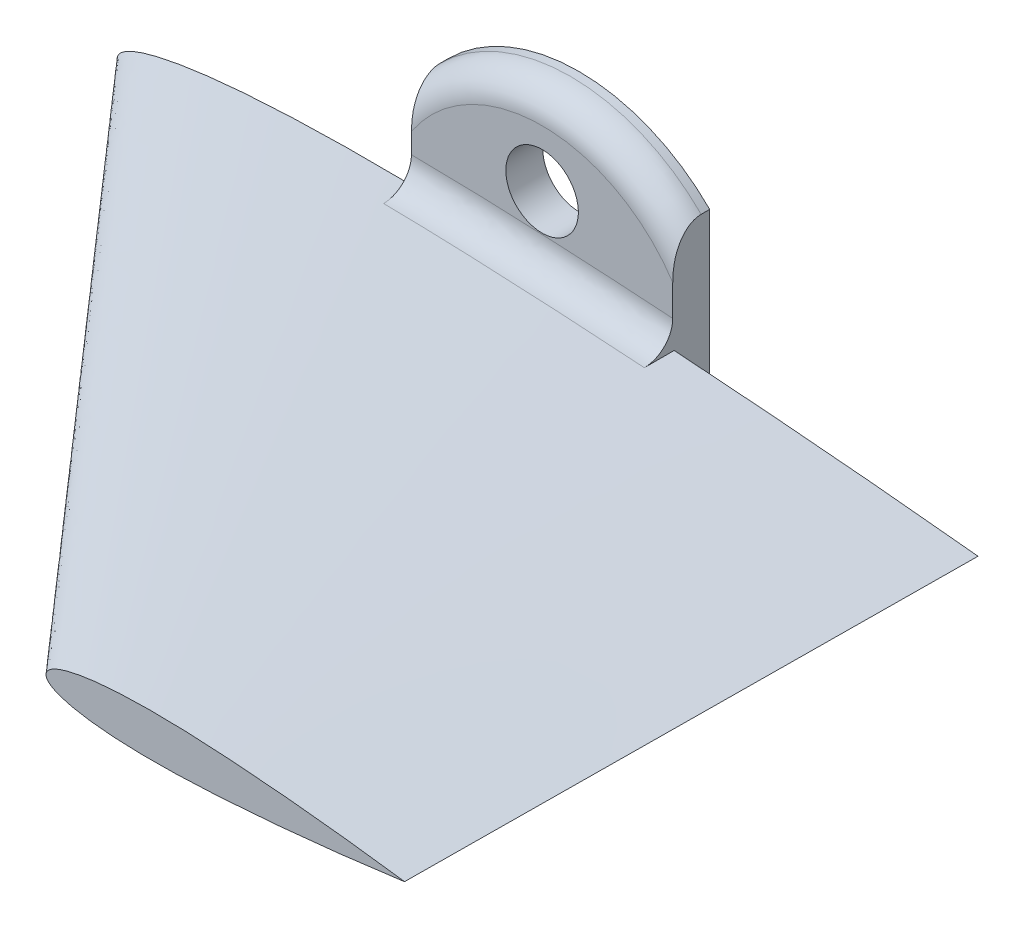
SolidWorks part; units mm, degrees
ref_plane "Front Plane" through (0, 0, 0) normal (0, 0, 1) x (1, 0, 0)
ref_plane "Top Plane" through (0, 0, 0) normal (0, 1, 0) x (1, 0, 0)
ref_plane "Right Plane" through (0, 0, 0) normal (1, 0, 0) x (0, 0, -1)
curve "BigAirfoilSketch"
  spline degree 3 poles (60, -0.0567, 0) (59.9883, -0.0579, 0) (59.9416, -0.0628, 0) (59.8367, -0.0739, 0) (59.6621, -0.0922, 0) (59.4182, -0.1176, 0) (59.1056, -0.15, 0) (58.725, -0.1892, 0) (58.2773, -0.2349, 0) (57.7636, -0.2868, 0) (57.1851, -0.3447, 0) (56.543, -0.4081, 0) (55.839, -0.4768, 0) (55.0746, -0.5503, 0) (54.2517, -0.6281, 0) (53.3721, -0.71, 0) (52.4379, -0.7954, 0) (51.4513, -0.884, 0) (50.4147, -0.9753, 0) (49.3303, -1.0688, 0) (48.2008, -1.1641, 0) (47.0288, -1.2607, 0) (45.817, -1.3582, 0) (44.5683, -1.4561, 0) (43.2855, -1.554, 0) (41.9717, -1.6513, 0) (40.63, -1.7476, 0) (39.2634, -1.8424, 0) (37.8752, -1.935, 0) (36.4686, -2.0251, 0) (35.0469, -2.112, 0) (33.6134, -2.1952, 0) (32.1715, -2.2742, 0) (30.7245, -2.3482, 0) (29.2758, -2.4169, 0) (27.8288, -2.4795, 0) (26.3868, -2.5354, 0) (24.9533, -2.5842, 0) (23.5316, -2.6253, 0) (22.125, -2.6582, 0) (20.7368, -2.6822, 0) (19.3702, -2.6971, 0) (18.0284, -2.7024, 0) (16.7146, -2.6978, 0) (15.4318, -2.6829, 0) (14.183, -2.6576, 0) (12.9711, -2.6217, 0) (11.799, -2.5751, 0) (10.6694, -2.5179, 0) (9.585, -2.4501, 0) (8.5482, -2.3718, 0) (7.5614, -2.2834, 0) (6.6271, -2.1852, 0) (5.7473, -2.0773, 0) (4.9241, -1.9604, 0) (4.1594, -1.8348, 0) (3.455, -1.7011, 0) (2.8124, -1.5597, 0) (2.2332, -1.4113, 0) (1.7185, -1.2562, 0) (1.2695, -1.0952, 0) (0.8868, -0.9286, 0) (0.5711, -0.7567, 0) (0.3223, -0.5794, 0) (0.1403, -0.3957, 0) (0.0264, -0.2025, 0) (-0.0125, 0, 0) (0.0264, 0.2025, 0) (0.1403, 0.3957, 0) (0.3223, 0.5794, 0) (0.5711, 0.7567, 0) (0.8868, 0.9286, 0) (1.2695, 1.0952, 0) (1.7185, 1.2562, 0) (2.2332, 1.4113, 0) (2.8124, 1.5597, 0) (3.455, 1.7011, 0) (4.1594, 1.8348, 0) (4.9241, 1.9604, 0) (5.7473, 2.0773, 0) (6.6271, 2.1852, 0) (7.5614, 2.2834, 0) (8.5482, 2.3718, 0) (9.585, 2.4501, 0) (10.6694, 2.5179, 0) (11.799, 2.5751, 0) (12.9711, 2.6217, 0) (14.183, 2.6576, 0) (15.4318, 2.6829, 0) (16.7146, 2.6978, 0) (18.0284, 2.7024, 0) (19.3702, 2.6971, 0) (20.7368, 2.6822, 0) (22.125, 2.6582, 0) (23.5316, 2.6253, 0) (24.9533, 2.5842, 0) (26.3868, 2.5354, 0) (27.8288, 2.4795, 0) (29.2758, 2.4169, 0) (30.7245, 2.3482, 0) (32.1715, 2.2742, 0) (33.6134, 2.1952, 0) (35.0469, 2.112, 0) (36.4686, 2.0251, 0) (37.8752, 1.935, 0) (39.2634, 1.8424, 0) (40.63, 1.7476, 0) (41.9717, 1.6513, 0) (43.2855, 1.554, 0) (44.5683, 1.4561, 0) (45.817, 1.3582, 0) (47.0288, 1.2607, 0) (48.2008, 1.1641, 0) (49.3303, 1.0688, 0) (50.4147, 0.9753, 0) (51.4513, 0.884, 0) (52.4379, 0.7954, 0) (53.3721, 0.71, 0) (54.2517, 0.6281, 0) (55.0746, 0.5503, 0) (55.839, 0.4768, 0) (56.543, 0.4081, 0) (57.1851, 0.3447, 0) (57.7636, 0.2868, 0) (58.2773, 0.2349, 0) (58.725, 0.1892, 0) (59.1056, 0.15, 0) (59.4182, 0.1176, 0) (59.6621, 0.0922, 0) (59.8367, 0.0739, 0) (59.9416, 0.0628, 0) (59.9883, 0.0579, 0) (60, 0.0567, 0) knots 0 0 0 0 0.00029 0.001159 0.002606 0.004627 0.007216 0.010369 0.014077 0.018331 0.023122 0.028438 0.034267 0.040595 0.047406 0.054685 0.062414 0.070576 0.079152 0.08812 0.09746 0.10715 0.117167 0.127488 0.138088 0.148943 0.160027 0.171315 0.182779 0.194393 0.206129 0.217961 0.22986 0.241798 0.253749 0.265683 0.277573 0.289392 0.301111 0.312704 0.324145 0.335405 0.346461 0.357287 0.367857 0.378149 0.388138 0.397803 0.407122 0.416074 0.424641 0.432803 0.440543 0.447846 0.454696 0.461079 0.466985 0.472404 0.477327 0.481752 0.485676 0.489104 0.49205 0.494541 0.496625 0.498395 0.5 0.501605 0.503375 0.505459 0.50795 0.510896 0.514324 0.518248 0.522673 0.527596 0.533015 0.538921 0.545304 0.552154 0.559457 0.567197 0.575359 0.583926 0.592878 0.602197 0.611862 0.621851 0.632143 0.642713 0.653539 0.664595 0.675855 0.687296 0.698889 0.710608 0.722427 0.734317 0.746251 0.758202 0.77014 0.782039 0.793871 0.805607 0.817221 0.828685 0.839973 0.851057 0.861912 0.872512 0.882833 0.89285 0.90254 0.91188 0.920848 0.929424 0.937586 0.945315 0.952594 0.959405 0.965733 0.971562 0.976878 0.981669 0.985923 0.989631 0.992784 0.995373 0.997394 0.998841 0.99971 1 1 1 1
sketch "Sketch11" plane through (0, 0, 0) normal (0, 0, 1) x (1, 0, 0)
  line L0 (59.9926, -0.0575) -> (60.5673, -0.003)
  line L1 (60, 0.0567) -> (60.5673, -0.003)
  spline S0 degree 3 poles (318.1925, -1983.0716) (92.5981, 4.8069) (76.3215, 1.6568) (59.8367, -0.0739) (59.4309, -0.1164) (58.9107, -0.1702) (58.0844, -0.2546) (57.3565, -0.3278) (56.543, -0.4081) (55.839, -0.4768) (55.0746, -0.5503) (54.2517, -0.6281) (53.3721, -0.71) (51.7306, -0.8601) (50.0055, -1.0118) (48.2008, -1.1641) (46.6123, -1.295) (44.9726, -1.4253) (42.8381, -1.5881) (40.6055, -1.751) (38.3313, -1.9058) (35.9906, -2.0557) (34.0879, -2.1693) (32.1715, -2.2742) (30.7245, -2.3482) (29.2758, -2.4169) (27.8288, -2.4795) (26.3868, -2.5354) (24.9533, -2.5842) (23.5316, -2.6253) (22.125, -2.6582) (20.7368, -2.6822) (19.3702, -2.6971) (18.0284, -2.7024) (16.7146, -2.6978) (15.4318, -2.6829) (14.183, -2.6576) (12.9711, -2.6217) (11.799, -2.5751) (10.6694, -2.5179) (9.585, -2.4501) (8.5482, -2.3718) (7.5614, -2.2834) (6.6271, -2.1852) (5.7473, -2.0773) (4.9241, -1.9604) (4.1594, -1.8348) (3.455, -1.7011) (2.8124, -1.5597) (2.2332, -1.4113) (1.7185, -1.2562) (1.2695, -1.0952) (0.8868, -0.9286) (0.5711, -0.7567) (0.3223, -0.5794) (0.1403, -0.3957) (0.0264, -0.2025) (-0.0125, 0) (0.0264, 0.2025) (0.1403, 0.3957) (0.3223, 0.5794) (0.5711, 0.7567) (0.8868, 0.9286) (1.2695, 1.0952) (1.7185, 1.2562) (2.2332, 1.4113) (2.8124, 1.5597) (3.455, 1.7011) (4.1594, 1.8348) (4.9241, 1.9604) (5.7473, 2.0773) (6.6271, 2.1852) (7.5614, 2.2834) (8.5482, 2.3718) (9.585, 2.4501) (10.6694, 2.5179) (11.799, 2.5751) (12.9711, 2.6217) (14.183, 2.6576) (15.4318, 2.6829) (16.7146, 2.6978) (18.0284, 2.7024) (19.3702, 2.6971) (20.7368, 2.6822) (22.125, 2.6582) (23.5316, 2.6253) (24.9533, 2.5842) (26.3868, 2.5354) (27.8288, 2.4795) (29.2758, 2.4169) (30.7245, 2.3482) (32.1715, 2.2742) (34.0879, 2.1693) (35.9906, 2.0557) (38.3313, 1.9058) (40.6055, 1.751) (43.2548, 1.5578) (45.3892, 1.3926) (47.0288, 1.2607) (48.2008, 1.1641) (49.6762, 1.0396) (51.0897, 0.9165) (52.4379, 0.7954) (53.3721, 0.71) (54.2517, 0.6281) (55.0746, 0.5503) (55.839, 0.4768) (56.543, 0.4081) (57.5059, 0.313) (58.465, 0.2162) (59.2912, 0.1308) (59.6621, 0.0922) (59.8367, 0.0739) (76.3212, -1.6567) (92.5976, -4.8068) (318.1829, 1982.9864) knots -0.406809 -0.406809 -0.406809 -0.406809 0.00029 0.001159 0.002606 0.010369 0.014077 0.023122 0.028438 0.034267 0.040595 0.047406 0.054685 0.062414 0.08812 0.09746 0.10715 0.127488 0.138088 0.160027 0.182779 0.194393 0.217961 0.22986 0.241798 0.253749 0.265683 0.277573 0.289392 0.301111 0.312704 0.324145 0.335405 0.346461 0.357287 0.367857 0.378149 0.388138 0.397803 0.407122 0.416074 0.424641 0.432803 0.440543 0.447846 0.454696 0.461079 0.466985 0.472404 0.477327 0.481752 0.485676 0.489104 0.49205 0.494541 0.496625 0.498395 0.5 0.501605 0.503375 0.505459 0.50795 0.510896 0.514324 0.518248 0.522673 0.527596 0.533015 0.538921 0.545304 0.552154 0.559457 0.567197 0.575359 0.583926 0.592878 0.602197 0.611862 0.621851 0.632143 0.642713 0.653539 0.664595 0.675855 0.687296 0.698889 0.710608 0.722427 0.734317 0.746251 0.758202 0.77014 0.782039 0.805607 0.817221 0.839973 0.861912 0.882833 0.89285 0.90254 0.91188 0.929424 0.937586 0.945315 0.952594 0.959405 0.965733 0.971562 0.976878 0.989631 0.995373 0.997394 0.998841 0.99971 1.406803 1.406803 1.406803 1.406803 only from (60, -0.0567) to (60, 0.0567) construction
  spline S1 degree 3 poles (59.9926, -0.0575) (59.9834, -0.0584) (59.9392, -0.0631) (59.8367, -0.0739) (59.4309, -0.1164) (58.9107, -0.1702) (58.0844, -0.2546) (57.3565, -0.3278) (56.543, -0.4081) (55.839, -0.4768) (55.0746, -0.5503) (54.2517, -0.6281) (53.3721, -0.71) (51.7306, -0.8601) (50.0055, -1.0118) (48.2008, -1.1641) (46.6123, -1.295) (44.9726, -1.4253) (42.8381, -1.5881) (40.6055, -1.751) (38.3313, -1.9058) (35.9906, -2.0557) (34.0879, -2.1693) (32.1715, -2.2742) (30.7245, -2.3482) (29.2758, -2.4169) (27.8288, -2.4795) (26.3868, -2.5354) (24.9533, -2.5842) (23.5316, -2.6253) (22.125, -2.6582) (20.7368, -2.6822) (19.3702, -2.6971) (18.0284, -2.7024) (16.7146, -2.6978) (15.4318, -2.6829) (14.183, -2.6576) (12.9711, -2.6217) (11.799, -2.5751) (10.6694, -2.5179) (9.585, -2.4501) (8.5482, -2.3718) (7.5614, -2.2834) (6.6271, -2.1852) (5.7473, -2.0773) (4.9241, -1.9604) (4.1594, -1.8348) (3.455, -1.7011) (2.8124, -1.5597) (2.2332, -1.4113) (1.7185, -1.2562) (1.2695, -1.0952) (0.8868, -0.9286) (0.5711, -0.7567) (0.3223, -0.5794) (0.1403, -0.3957) (0.0264, -0.2025) (-0.0125, 0) (0.0264, 0.2025) (0.1403, 0.3957) (0.3223, 0.5794) (0.5711, 0.7567) (0.8868, 0.9286) (1.2695, 1.0952) (1.7185, 1.2562) (2.2332, 1.4113) (2.8124, 1.5597) (3.455, 1.7011) (4.1594, 1.8348) (4.9241, 1.9604) (5.7473, 2.0773) (6.6271, 2.1852) (7.5614, 2.2834) (8.5482, 2.3718) (9.585, 2.4501) (10.6694, 2.5179) (11.799, 2.5751) (12.9711, 2.6217) (14.183, 2.6576) (15.4318, 2.6829) (16.7146, 2.6978) (18.0284, 2.7024) (19.3702, 2.6971) (20.7368, 2.6822) (22.125, 2.6582) (23.5316, 2.6253) (24.9533, 2.5842) (26.3868, 2.5354) (27.8288, 2.4795) (29.2758, 2.4169) (30.7245, 2.3482) (32.1715, 2.2742) (34.0879, 2.1693) (35.9906, 2.0557) (38.3313, 1.9058) (40.6055, 1.751) (43.2548, 1.5578) (45.3892, 1.3926) (47.0288, 1.2607) (48.2008, 1.1641) (49.6762, 1.0396) (51.0897, 0.9165) (52.4379, 0.7954) (53.3721, 0.71) (54.2517, 0.6281) (55.0746, 0.5503) (55.839, 0.4768) (56.543, 0.4081) (57.5059, 0.313) (58.465, 0.2162) (59.2912, 0.1308) (59.6621, 0.0922) (59.8367, 0.0739) (59.9416, 0.0628) (59.9883, 0.0579) (60, 0.0567) knots 0.000061 0.000061 0.000061 0.000061 0.00029 0.001159 0.002606 0.010369 0.014077 0.023122 0.028438 0.034267 0.040595 0.047406 0.054685 0.062414 0.08812 0.09746 0.10715 0.127488 0.138088 0.160027 0.182779 0.194393 0.217961 0.22986 0.241798 0.253749 0.265683 0.277573 0.289392 0.301111 0.312704 0.324145 0.335405 0.346461 0.357287 0.367857 0.378149 0.388138 0.397803 0.407122 0.416074 0.424641 0.432803 0.440543 0.447846 0.454696 0.461079 0.466985 0.472404 0.477327 0.481752 0.485676 0.489104 0.49205 0.494541 0.496625 0.498395 0.5 0.501605 0.503375 0.505459 0.50795 0.510896 0.514324 0.518248 0.522673 0.527596 0.533015 0.538921 0.545304 0.552154 0.559457 0.567197 0.575359 0.583926 0.592878 0.602197 0.611862 0.621851 0.632143 0.642713 0.653539 0.664595 0.675855 0.687296 0.698889 0.710608 0.722427 0.734317 0.746251 0.758202 0.77014 0.782039 0.805607 0.817221 0.839973 0.861912 0.882833 0.89285 0.90254 0.91188 0.929424 0.937586 0.945315 0.952594 0.959405 0.965733 0.971562 0.976878 0.989631 0.995373 0.997394 0.998841 0.99971 1 1 1 1
curve "SmallAirfoilSketch"
  spline degree 3 poles (60, -0.0315, 40) (59.9951, -0.0322, 40) (59.9757, -0.0349, 40) (59.932, -0.041, 40) (59.8592, -0.0512, 40) (59.7576, -0.0653, 40) (59.6273, -0.0833, 40) (59.4688, -0.1051, 40) (59.2822, -0.1305, 40) (59.0682, -0.1594, 40) (58.8271, -0.1915, 40) (58.5596, -0.2267, 40) (58.2663, -0.2649, 40) (57.9478, -0.3057, 40) (57.6049, -0.349, 40) (57.2384, -0.3944, 40) (56.8492, -0.4419, 40) (56.4381, -0.4911, 40) (56.0061, -0.5418, 40) (55.5543, -0.5938, 40) (55.0837, -0.6467, 40) (54.5954, -0.7004, 40) (54.0904, -0.7546, 40) (53.5701, -0.809, 40) (53.0357, -0.8633, 40) (52.4883, -0.9174, 40) (51.9292, -0.9709, 40) (51.3598, -1.0235, 40) (50.7814, -1.075, 40) (50.1953, -1.1251, 40) (49.6029, -1.1733, 40) (49.0056, -1.2196, 40) (48.4048, -1.2634, 40) (47.8019, -1.3046, 40) (47.1983, -1.3427, 40) (46.5954, -1.3775, 40) (45.9946, -1.4086, 40) (45.3973, -1.4357, 40) (44.8049, -1.4585, 40) (44.2188, -1.4768, 40) (43.6403, -1.4901, 40) (43.0709, -1.4984, 40) (42.5118, -1.5014, 40) (41.9644, -1.4988, 40) (41.4299, -1.4905, 40) (40.9095, -1.4764, 40) (40.4046, -1.4565, 40) (39.9162, -1.4306, 40) (39.4455, -1.3988, 40) (38.9936, -1.3611, 40) (38.5615, -1.3177, 40) (38.1504, -1.2685, 40) (37.761, -1.2139, 40) (37.3944, -1.154, 40) (37.0513, -1.089, 40) (36.7326, -1.0192, 40) (36.439, -0.9449, 40) (36.1711, -0.8663, 40) (35.9296, -0.7837, 40) (35.7149, -0.6974, 40) (35.5275, -0.6077, 40) (35.3678, -0.5148, 40) (35.2359, -0.4187, 40) (35.132, -0.3194, 40) (35.0565, -0.2165, 40) (35.0103, -0.1097, 40) (34.995, 0, 40) (35.0103, 0.1097, 40) (35.0565, 0.2165, 40) (35.132, 0.3194, 40) (35.2359, 0.4187, 40) (35.3678, 0.5148, 40) (35.5275, 0.6077, 40) (35.7149, 0.6974, 40) (35.9296, 0.7837, 40) (36.1711, 0.8663, 40) (36.439, 0.9449, 40) (36.7326, 1.0192, 40) (37.0513, 1.089, 40) (37.3944, 1.154, 40) (37.761, 1.2139, 40) (38.1504, 1.2685, 40) (38.5615, 1.3177, 40) (38.9936, 1.3611, 40) (39.4455, 1.3988, 40) (39.9162, 1.4306, 40) (40.4046, 1.4565, 40) (40.9095, 1.4764, 40) (41.4299, 1.4905, 40) (41.9644, 1.4988, 40) (42.5118, 1.5014, 40) (43.0709, 1.4984, 40) (43.6403, 1.4901, 40) (44.2188, 1.4768, 40) (44.8049, 1.4585, 40) (45.3973, 1.4357, 40) (45.9946, 1.4086, 40) (46.5954, 1.3775, 40) (47.1983, 1.3427, 40) (47.8019, 1.3046, 40) (48.4048, 1.2634, 40) (49.0056, 1.2196, 40) (49.6029, 1.1733, 40) (50.1953, 1.1251, 40) (50.7814, 1.075, 40) (51.3598, 1.0235, 40) (51.9292, 0.9709, 40) (52.4883, 0.9174, 40) (53.0357, 0.8633, 40) (53.5701, 0.809, 40) (54.0904, 0.7546, 40) (54.5954, 0.7004, 40) (55.0837, 0.6467, 40) (55.5543, 0.5938, 40) (56.0061, 0.5418, 40) (56.4381, 0.4911, 40) (56.8492, 0.4419, 40) (57.2384, 0.3944, 40) (57.6049, 0.349, 40) (57.9478, 0.3057, 40) (58.2663, 0.2649, 40) (58.5596, 0.2267, 40) (58.8271, 0.1915, 40) (59.0682, 0.1594, 40) (59.2822, 0.1305, 40) (59.4688, 0.1051, 40) (59.6273, 0.0833, 40) (59.7576, 0.0653, 40) (59.8592, 0.0512, 40) (59.932, 0.041, 40) (59.9757, 0.0349, 40) (59.9951, 0.0322, 40) (60, 0.0315, 40) knots 0 0 0 0 0.000289 0.001156 0.002598 0.004612 0.007194 0.010336 0.014031 0.018271 0.023046 0.028343 0.03415 0.040454 0.047239 0.054489 0.062186 0.070314 0.078852 0.08778 0.097077 0.106722 0.116691 0.126961 0.137507 0.148306 0.159331 0.170557 0.181957 0.193504 0.205172 0.216932 0.228758 0.240621 0.252495 0.26435 0.276161 0.287898 0.299536 0.311047 0.322405 0.333584 0.344559 0.355306 0.3658 0.376018 0.385938 0.395538 0.404798 0.413699 0.422222 0.430349 0.438066 0.445357 0.452209 0.458611 0.464554 0.47003 0.475035 0.479569 0.483637 0.48725 0.490432 0.493219 0.495674 0.497891 0.5 0.502109 0.504326 0.506781 0.509568 0.51275 0.516363 0.520431 0.524965 0.52997 0.535446 0.541389 0.547791 0.554643 0.561934 0.569651 0.577778 0.586301 0.595202 0.604462 0.614062 0.623982 0.6342 0.644694 0.655441 0.666416 0.677595 0.688953 0.700464 0.712102 0.723839 0.73565 0.747505 0.759379 0.771242 0.783068 0.794828 0.806496 0.818043 0.829443 0.840669 0.851694 0.862493 0.873039 0.883309 0.893278 0.902923 0.91222 0.921148 0.929686 0.937814 0.945511 0.952761 0.959546 0.96585 0.971657 0.976954 0.981729 0.985969 0.989664 0.992806 0.995388 0.997402 0.998844 0.999711 1 1 1 1
ref_plane "SmallAirfoilPlane" through (0, 0, 40) normal (0, 0, 1) x (1, 0, 0)
sketch "Sketch16" plane through (0, 0, 40) normal (0, 0, 1) x (1, 0, 0)
  line L0 (60, 0.0315) -> (60.2245, 0)
  line L1 (60, -0.0315) -> (60.2245, 0)
  spline S0 degree 3 poles (362.023, -1976.9223) (76.0847, 3.4344) (68.104, 1.1028) (59.932, -0.041) (59.7629, -0.0647) (59.3944, -0.1155) (58.9608, -0.1739) (58.5596, -0.2267) (58.2663, -0.2649) (57.2644, -0.3932) (56.2027, -0.5208) (54.9154, -0.6656) (54.0753, -0.7569) (53.023, -0.8654) (51.9191, -0.9728) (50.9714, -1.0588) (49.9962, -1.1421) (49.0024, -1.2211) (48.0025, -1.2919) (46.998, -1.3553) (46.1958, -1.3994) (45.3973, -1.4357) (44.8049, -1.4585) (44.2188, -1.4768) (43.6403, -1.4901) (43.0709, -1.4984) (42.5118, -1.5014) (41.9644, -1.4988) (41.4299, -1.4905) (40.9095, -1.4764) (40.4046, -1.4565) (39.9162, -1.4306) (39.4455, -1.3988) (38.9936, -1.3611) (38.5615, -1.3177) (38.1504, -1.2685) (37.761, -1.2139) (37.3944, -1.154) (37.0513, -1.089) (36.7326, -1.0192) (36.439, -0.9449) (36.1711, -0.8663) (35.9296, -0.7837) (35.7149, -0.6974) (35.5275, -0.6077) (35.3678, -0.5148) (35.2359, -0.4187) (35.132, -0.3194) (35.0565, -0.2165) (35.0103, -0.1097) (34.995, 0) (35.0103, 0.1097) (35.0565, 0.2165) (35.132, 0.3194) (35.2359, 0.4187) (35.3678, 0.5148) (35.5275, 0.6077) (35.7149, 0.6974) (35.9296, 0.7837) (36.1711, 0.8663) (36.439, 0.9449) (36.7326, 1.0192) (37.0513, 1.089) (37.3944, 1.154) (37.761, 1.2139) (38.1504, 1.2685) (38.5615, 1.3177) (38.9936, 1.3611) (39.4455, 1.3988) (39.9162, 1.4306) (40.4046, 1.4565) (40.9095, 1.4764) (41.4299, 1.4905) (41.9644, 1.4988) (42.5118, 1.5014) (43.0709, 1.4984) (43.6403, 1.4901) (44.2188, 1.4768) (44.8049, 1.4585) (45.3973, 1.4357) (46.1958, 1.3994) (46.998, 1.3553) (48.0025, 1.2919) (49.0024, 1.2211) (50.1893, 1.1267) (51.1644, 1.0416) (52.1119, 0.954) (53.1916, 0.849) (54.5518, 0.7068) (55.8237, 0.5639) (56.942, 0.4314) (57.6958, 0.338) (58.2663, 0.2649) (58.7115, 0.207) (59.1656, 0.1465) (59.599, 0.0873) (59.8158, 0.0573) (59.932, 0.041) (68.1039, -1.1028) (76.0847, -3.4344) (362.0211, 1976.9099) knots -0.482993 -0.482993 -0.482993 -0.482993 0.000289 0.001156 0.002598 0.010336 0.023046 0.028343 0.03415 0.040454 0.08778 0.097077 0.116691 0.137507 0.159331 0.181957 0.193504 0.216932 0.240621 0.252495 0.276161 0.287898 0.299536 0.311047 0.322405 0.333584 0.344559 0.355306 0.3658 0.376018 0.385938 0.395538 0.404798 0.413699 0.422222 0.430349 0.438066 0.445357 0.452209 0.458611 0.464554 0.47003 0.475035 0.479569 0.483637 0.48725 0.490432 0.493219 0.495674 0.497891 0.5 0.502109 0.504326 0.506781 0.509568 0.51275 0.516363 0.520431 0.524965 0.52997 0.535446 0.541389 0.547791 0.554643 0.561934 0.569651 0.577778 0.586301 0.595202 0.604462 0.614062 0.623982 0.6342 0.644694 0.655441 0.666416 0.677595 0.688953 0.700464 0.712102 0.723839 0.747505 0.759379 0.783068 0.806496 0.829443 0.840669 0.862493 0.893278 0.921148 0.937814 0.959546 0.96585 0.971657 0.985969 0.992806 0.997402 0.998844 0.999711 1.482992 1.482992 1.482992 1.482992 only from (60, -0.0315) to (60, 0.0315) construction
  spline S1 degree 3 poles (60, -0.0315) (59.9951, -0.0322) (59.9757, -0.0349) (59.932, -0.041) (59.7629, -0.0647) (59.3944, -0.1155) (58.9608, -0.1739) (58.5596, -0.2267) (58.2663, -0.2649) (57.2644, -0.3932) (56.2027, -0.5208) (54.9154, -0.6656) (54.0753, -0.7569) (53.023, -0.8654) (51.9191, -0.9728) (50.9714, -1.0588) (49.9962, -1.1421) (49.0024, -1.2211) (48.0025, -1.2919) (46.998, -1.3553) (46.1958, -1.3994) (45.3973, -1.4357) (44.8049, -1.4585) (44.2188, -1.4768) (43.6403, -1.4901) (43.0709, -1.4984) (42.5118, -1.5014) (41.9644, -1.4988) (41.4299, -1.4905) (40.9095, -1.4764) (40.4046, -1.4565) (39.9162, -1.4306) (39.4455, -1.3988) (38.9936, -1.3611) (38.5615, -1.3177) (38.1504, -1.2685) (37.761, -1.2139) (37.3944, -1.154) (37.0513, -1.089) (36.7326, -1.0192) (36.439, -0.9449) (36.1711, -0.8663) (35.9296, -0.7837) (35.7149, -0.6974) (35.5275, -0.6077) (35.3678, -0.5148) (35.2359, -0.4187) (35.132, -0.3194) (35.0565, -0.2165) (35.0103, -0.1097) (34.995, 0) (35.0103, 0.1097) (35.0565, 0.2165) (35.132, 0.3194) (35.2359, 0.4187) (35.3678, 0.5148) (35.5275, 0.6077) (35.7149, 0.6974) (35.9296, 0.7837) (36.1711, 0.8663) (36.439, 0.9449) (36.7326, 1.0192) (37.0513, 1.089) (37.3944, 1.154) (37.761, 1.2139) (38.1504, 1.2685) (38.5615, 1.3177) (38.9936, 1.3611) (39.4455, 1.3988) (39.9162, 1.4306) (40.4046, 1.4565) (40.9095, 1.4764) (41.4299, 1.4905) (41.9644, 1.4988) (42.5118, 1.5014) (43.0709, 1.4984) (43.6403, 1.4901) (44.2188, 1.4768) (44.8049, 1.4585) (45.3973, 1.4357) (46.1958, 1.3994) (46.998, 1.3553) (48.0025, 1.2919) (49.0024, 1.2211) (50.1893, 1.1267) (51.1644, 1.0416) (52.1119, 0.954) (53.1916, 0.849) (54.5518, 0.7068) (55.8237, 0.5639) (56.942, 0.4314) (57.6958, 0.338) (58.2663, 0.2649) (58.7115, 0.207) (59.1656, 0.1465) (59.599, 0.0873) (59.8158, 0.0573) (59.932, 0.041) (59.9757, 0.0349) (59.9951, 0.0322) (60, 0.0315) knots 0 0 0 0 0.000289 0.001156 0.002598 0.010336 0.023046 0.028343 0.03415 0.040454 0.08778 0.097077 0.116691 0.137507 0.159331 0.181957 0.193504 0.216932 0.240621 0.252495 0.276161 0.287898 0.299536 0.311047 0.322405 0.333584 0.344559 0.355306 0.3658 0.376018 0.385938 0.395538 0.404798 0.413699 0.422222 0.430349 0.438066 0.445357 0.452209 0.458611 0.464554 0.47003 0.475035 0.479569 0.483637 0.48725 0.490432 0.493219 0.495674 0.497891 0.5 0.502109 0.504326 0.506781 0.509568 0.51275 0.516363 0.520431 0.524965 0.52997 0.535446 0.541389 0.547791 0.554643 0.561934 0.569651 0.577778 0.586301 0.595202 0.604462 0.614062 0.623982 0.6342 0.644694 0.655441 0.666416 0.677595 0.688953 0.700464 0.712102 0.723839 0.747505 0.759379 0.783068 0.806496 0.829443 0.840669 0.862493 0.893278 0.921148 0.937814 0.959546 0.96585 0.971657 0.985969 0.992806 0.997402 0.998844 0.999711 1 1 1 1
loft "AirfoilLoftExtrude" add profiles "Sketch11", "Sketch16"
sketch "Sketch17" plane through (0, 0, 0) normal (0, 0, -1) x (-1, 0, 0)
  line L1 (-39.1924, -9.1924) -> (-39.1924, 9.1924)
  line L3 (-20.8076, 9.1924) -> (-20.8076, -9.1924)
  arc A0 (-20.8076, 9.1924) -> (-39.1924, 9.1924) centre (-30, 0) ccw
  arc A1 (-39.1924, -9.1924) -> (-20.8076, -9.1924) centre (-30, 0) ccw
  dimension "D2" = 26
  dimension "D1" = 30
extrude "ServoMountExtrude" add sketch "Sketch17" along normal blind 2.5 and the other way blind 0.1 contours A0 L1 A1 L3
fillet "Fillet8" radius 2 4 edges at (21.9211, -2.6589, 0.1) (33.635, 2.193, 0.1) (30, 13, 0.1) (30, -13, 0.1)
sketch "Sketch18" plane through (0, 0, -2.5) normal (0, 0, -1) x (-1, 0, 0)
  line L0 (-39.1924, -9.1924) -> (-39.1924, 9.1924) construction
  circle A2 centre (-30, 7) radius 2.55
  circle A3 centre (-30, -7) radius 2.55
  dimension "D1" = 5.1
  dimension "D3" = 5.1
  dimension "D2" = 9.1924
  dimension "D4" = 14
extrude "Cut-Extrude1" cut sketch "Sketch18" against normal through all
